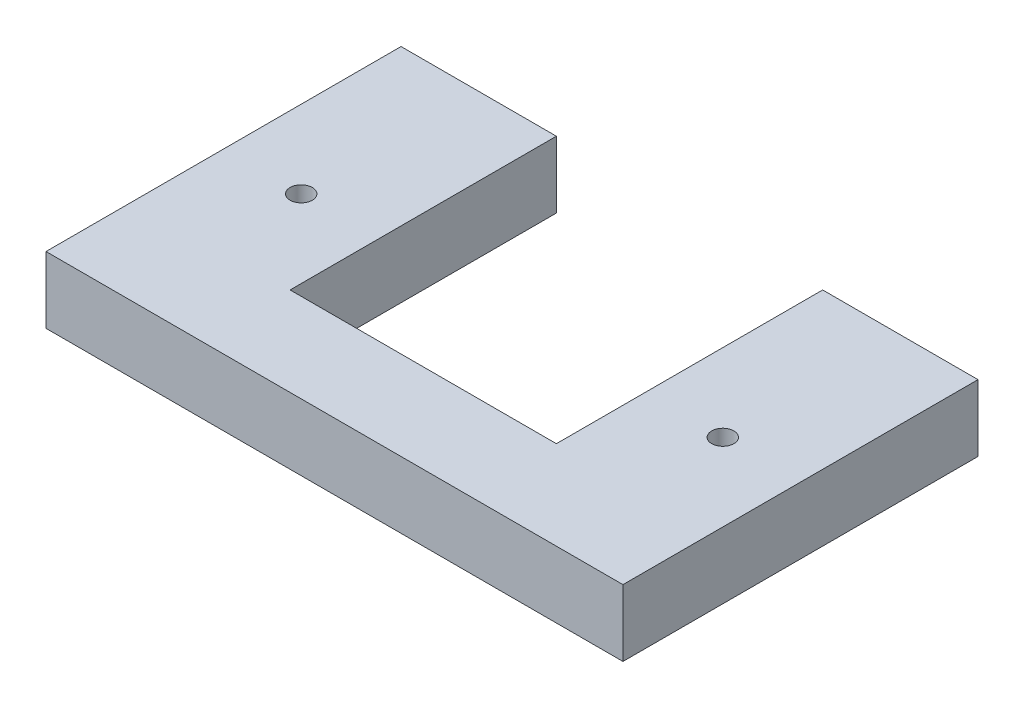
SolidWorks part; units mm, degrees
ref_plane "Front Plane" through (0, 0, 0) normal (0, 0, 1) x (1, 0, 0)
ref_plane "Top Plane" through (0, 0, 0) normal (0, 1, 0) x (1, 0, 0)
ref_plane "Right Plane" through (0, 0, 0) normal (1, 0, 0) x (0, 0, -1)
sketch "Sketch1" plane through (0, 0, 0) normal (0, 1, 0) x (1, 0, 0)
  line L1 (-82.55, -50.8) -> (82.55, -50.8)
  line L2 (-82.55, -50.8) -> (-82.55, 50.8)
  line L3 (-82.55, 50.8) -> (82.55, 50.8)
  line L4 (82.55, -50.8) -> (82.55, 50.8)
  line L5 (-82.55, -50.8) -> (82.55, 50.8) construction
  line L6 (-82.55, 50.8) -> (82.55, -50.8) construction
  point P0 (0, 0)
  dimension "D1" = 165.1
  dimension "D2" = 101.6
extrude "Boss-Extrude1" add sketch "Sketch1" along normal blind 19.05
sketch "Sketch2" plane through (0, 19.05, 0) normal (0, 1, 0) x (1, 0, 0)
  line L0 (82.55, 50.8) -> (-82.55, 50.8) construction
  line L1 (-38.1, 50.8) -> (38.1, 50.8)
  line L2 (-38.1, 50.8) -> (-38.1, -25.4)
  line L3 (-38.1, -25.4) -> (38.1, -25.4)
  line L4 (38.1, 50.8) -> (38.1, -25.4)
  line L5 (-82.55, 50.8) -> (-82.55, -50.8) construction
  line L6 (82.55, -50.8) -> (82.55, 50.8) construction
  line L7 (-82.55, -50.8) -> (82.55, -50.8) construction
  dimension "D1" = 44.45
  dimension "D2" = 44.45
  dimension "D3" = 25.4
extrude "Cut-Extrude1" cut sketch "Sketch2" against normal through all
sketch "Sketch3" plane through (0, 19.05, 0) normal (0, 1, 0) x (1, 0, 0)
  line L0 (-38.1, 50.8) -> (-82.55, 50.8) construction
  line L1 (82.55, 50.8) -> (38.1, 50.8) construction
  circle A0 centre (-60.325, 0) radius 3.175
  circle A1 centre (60.325, 0) radius 3.175
  dimension "D1" = 6.35
  dimension "D2" = 6.35
  dimension "D3" = 120.65
  dimension "D4" = 60.325
  dimension "D5" = 50.8
  dimension "D6" = 50.8
extrude "Cut-Extrude2" cut sketch "Sketch3" against normal blind 15.875
